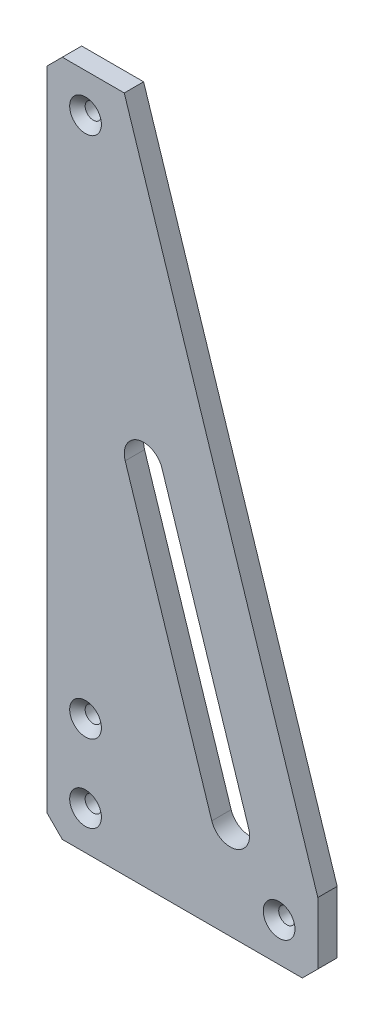
SolidWorks part; units mm, degrees
ref_plane "前视基准面" through (0, 0, 0) normal (0, 0, 1) x (1, 0, 0)
ref_plane "上视基准面" through (0, 0, 0) normal (0, 1, 0) x (1, 0, 0)
ref_plane "右视基准面" through (0, 0, 0) normal (1, 0, 0) x (0, 0, -1)
sketch "草图1" plane through (0, 0, 0) normal (0, 0, 1) x (1, 0, 0)
  line L0 (-35, 87.5) -> (-35, -87.5)
  line L1 (-35, -87.5) -> (35, -87.5)
  line L2 (35, -87.5) -> (35, -67.5)
  line L3 (35, -67.5) -> (-15, 87.5)
  line L4 (-15, 87.5) -> (-35, 87.5)
  line L5 (25, -77.5) -> (-25, -77.5) construction
  line L6 (-25, -77.5) -> (-25, -57.5) construction
  line L7 (-25, -57.5) -> (-25, 77.5) construction
  circle A0 centre (-25, -77.5) radius 2.1
  circle A1 centre (25, -77.5) radius 2.1
  circle A2 centre (-25, 77.5) radius 2.1
  circle A3 centre (-25, -57.5) radius 2.1
  point P0 (-35, 0)
  point P7 (0, -87.5)
  dimension "D3" = 10
  dimension "D6" = 10
  dimension "D7" = 4.2
  dimension "D1" = 20
  dimension "D2" = 20
  dimension "D4" = 10
  dimension "D5" = 10
  dimension "D8" = 175
  dimension "D9" = 70
  dimension "D10" = 20
extrude "凸台-拉伸1" add sketch "草图1" along normal mid plane 5
chamfer "倒角1" distance 4 angle 45 3 edges at (35, -87.5, 0) (-35, -87.5, 0) (-35, 87.5, 0)
chamfer "倒角2" distance 2 angle 45 4 edges at (-22.9, 77.5, 2.5) (27.1, -77.5, 2.5) (-22.9, -57.5, 2.5) (-22.9, -77.5, 2.5)
sketch "草图2" plane through (0, 0, -2.5) normal (0, 0, -1) x (-1, 0, 0)
  line L0 (-12.3723, -62.5) -> (10, 6.854) construction
  line L1 (-17.1308, -60.965) -> (5.2415, 8.389)
  line L2 (-7.6137, -64.035) -> (14.7585, 5.319)
  line L3 (-35, -67.5) -> (15, 87.5) construction
  line L4 (35, 83.5) -> (35, -83.5) construction
  arc A0 (-17.1308, -60.965) -> (-7.6137, -64.035) centre (-12.3723, -62.5) ccw
  arc A1 (14.7585, 5.319) -> (5.2415, 8.389) centre (10, 6.854) ccw
  circle A4 centre (-25, -77.5) radius 2.1 construction
  point P2 (-1.1861, -27.823)
  dimension "D2" = 5
  dimension "D3" = 15
  dimension "D1" = 15
  dimension "D4" = 25
extrude "切除-拉伸1" cut sketch "草图2" against normal through all
